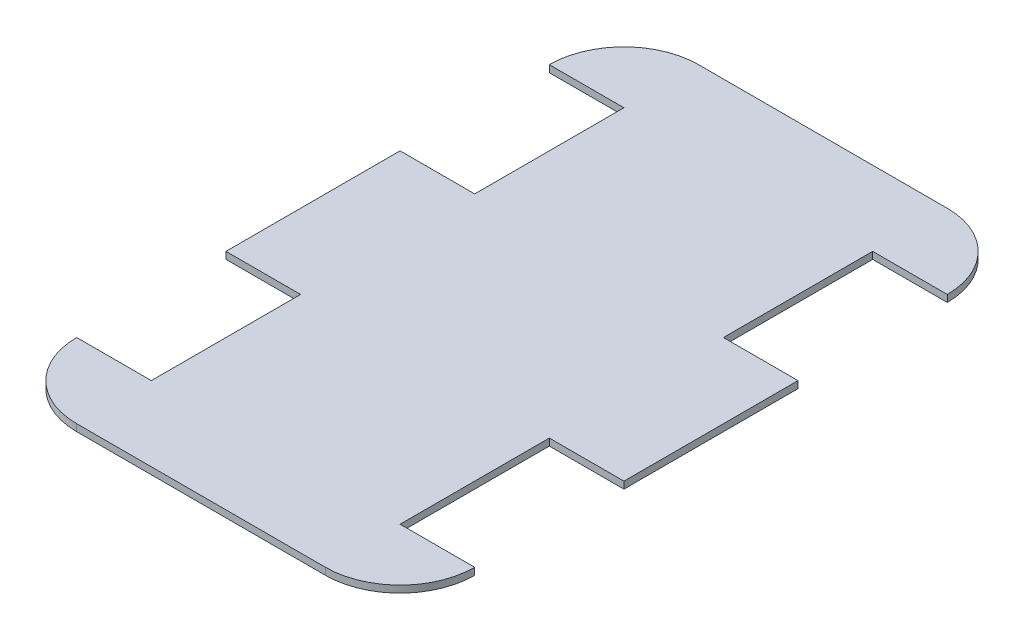
SolidWorks part; units mm, degrees
ref_plane "Front Plane" through (0, 0, 0) normal (0, 0, 1) x (1, 0, 0)
ref_plane "Top Plane" through (0, 0, 0) normal (0, 1, 0) x (1, 0, 0)
ref_plane "Right Plane" through (0, 0, 0) normal (1, 0, 0) x (0, 0, -1)
sketch "Sketch1" plane through (0, 0, 0) normal (0, 1, 0) x (1, 0, 0)
  line L0 (0, 30) -> (30, 30)
  line L1 (30, 0) -> (130, 0)
  line L2 (0, 90) -> (0, 160)
  line L3 (30, 250) -> (130, 250)
  line L4 (160, 90) -> (160, 160)
  line L5 (30, 30) -> (30, 90)
  line L6 (30, 90) -> (0, 90)
  line L7 (0, 220) -> (30, 220)
  line L8 (30, 220) -> (30, 160)
  line L9 (30, 160) -> (0, 160)
  line L10 (160, 220) -> (130, 220)
  line L11 (130, 220) -> (130, 160)
  line L12 (130, 160) -> (160, 160)
  line L13 (160, 90) -> (130, 90)
  line L14 (130, 90) -> (130, 30)
  line L15 (130, 30) -> (160, 30)
  arc A0 (0, 220) -> (30, 250) centre (30, 220) cw
  arc A1 (160, 220) -> (130, 250) centre (130, 220) ccw
  arc A2 (160, 30) -> (130, 0) centre (130, 30) cw
  arc A3 (0, 30) -> (30, 0) centre (30, 30) ccw
  point P8 (0, 250)
  point P11 (160, 250)
  point P14 (160, 0)
  point P17 (0, 0)
  dimension "D3" = 30
  dimension "D4" = 30
  dimension "D5" = 30
  dimension "D6" = 30
  dimension "D1" = 160
  dimension "D2" = 250
  dimension "D7" = 60
  dimension "D8" = 30
  dimension "D9" = 30
  dimension "D10" = 60
  dimension "D11" = 60
  dimension "D12" = 30
  dimension "D13" = 30
  dimension "D14" = 60
extrude "Boss-Extrude1" add sketch "Sketch1" along normal blind 2.8
